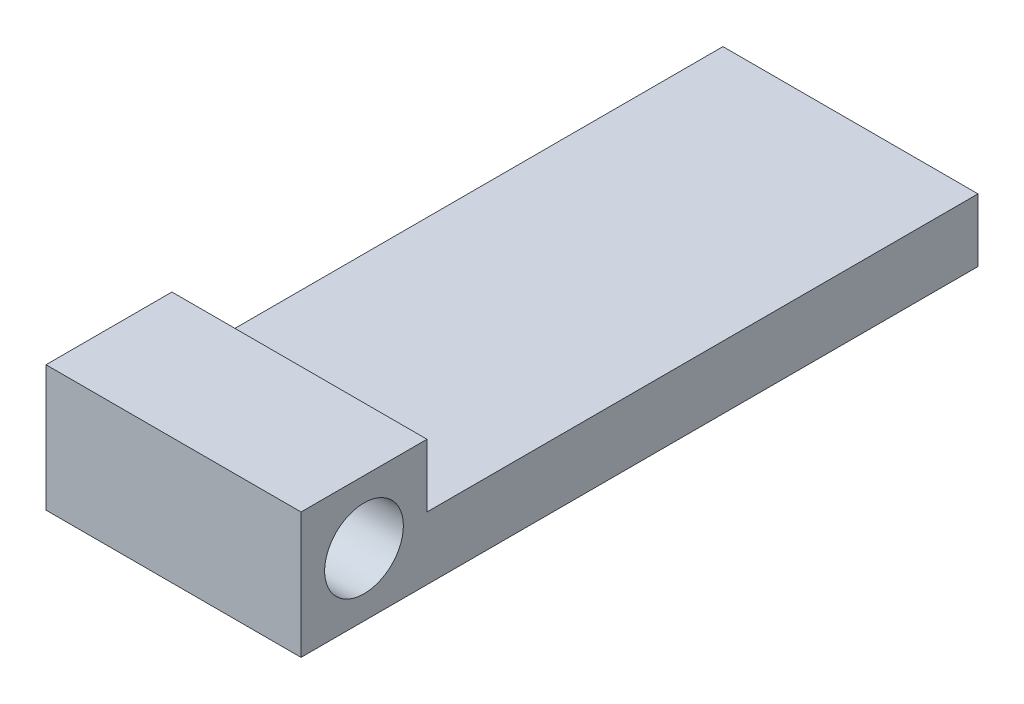
SolidWorks part; units mm, degrees
ref_plane "Front Plane" through (0, 0, 0) normal (0, 0, 1) x (1, 0, 0)
ref_plane "Top Plane" through (0, 0, 0) normal (0, 1, 0) x (1, 0, 0)
ref_plane "Right Plane" through (0, 0, 0) normal (1, 0, 0) x (0, 0, -1)
sketch "Sketch1" plane through (0, 0, 0) normal (0, 1, 0) x (1, 0, 0)
  line L1 (0, 0) -> (8.1, 0)
  line L2 (0, 0) -> (0, 4)
  line L3 (0, 4) -> (8.1, 4)
  line L4 (8.1, 0) -> (8.1, 4)
  dimension "D1" = 8.1
  dimension "22" = 4
extrude "Boss-Extrude1" add sketch "Sketch1" along normal blind 4
sketch "Sketch2" plane through (8.1, 0, 0) normal (1, 0, 0) x (0, 0, -1)
  line L0 (0, 4) -> (0, 0) construction
  line L1 (0, 0) -> (4, 0) construction
  circle A0 centre (2, 2) radius 1.25
  dimension "D1" = 2
  dimension "D2" = 2
extrude "Cut-Extrude1" cut sketch "Sketch2" against normal blind 9
sketch "Sketch3" plane through (0, 4, 0) normal (0, 1, 0) x (1, 0, 0)
sketch "Sketch4" plane through (0, 0, 0) normal (0, -1, 0) x (-1, 0, 0)
  line L0 (-8.1, 0) -> (-8.1, 4) construction
  line L1 (0, 4) -> (-8.1, 4)
  line L2 (0, 4) -> (0, 21.5)
  line L3 (0, 21.5) -> (-8.1, 21.5)
  line L4 (-8.1, 4) -> (-8.1, 21.5)
  dimension "D1" = 17.5
extrude "Boss-Extrude2" add sketch "Sketch4" against normal blind 2
